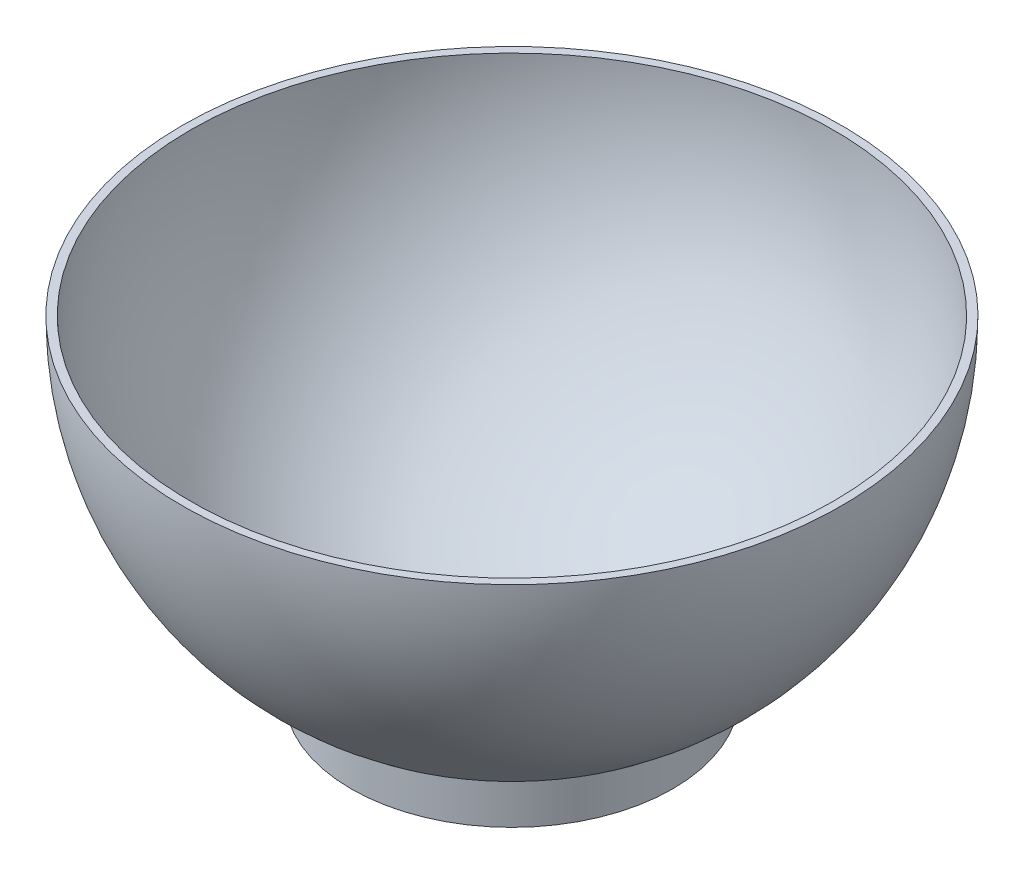
SolidWorks part; units mm, degrees
ref_plane "Front Plane" through (0, 0, 0) normal (0, 0, 1) x (1, 0, 0)
ref_plane "Top Plane" through (0, 0, 0) normal (0, 1, 0) x (1, 0, 0)
ref_plane "Right Plane" through (0, 0, 0) normal (1, 0, 0) x (0, 0, -1)
sketch "Sketch1" plane through (0, 0, 0) normal (0, 0, 1) x (1, 0, 0)
  line L0 (0, 0) -> (0, -3.175)
  line L1 (127, 127) -> (130.175, 127)
  line L2 (0, -3.175) -> (63.5, -3.175)
  line L3 (63.5, -3.175) -> (63.5, 13.3634)
  arc A0 (0, 0) -> (127, 127) centre (0, 127) ccw
  arc A1 (0, -3.175) -> (130.175, 127) centre (0, 127) ccw
  arc A2 (0, -3.175) -> (63.5, 13.3634) centre (0, 127) ccw
  dimension "D1" = 127
  dimension "D2" = 3.175
  dimension "D3" = 63.5
revolve "Revolve1" add sketch "Sketch1" angle 360 about L0
